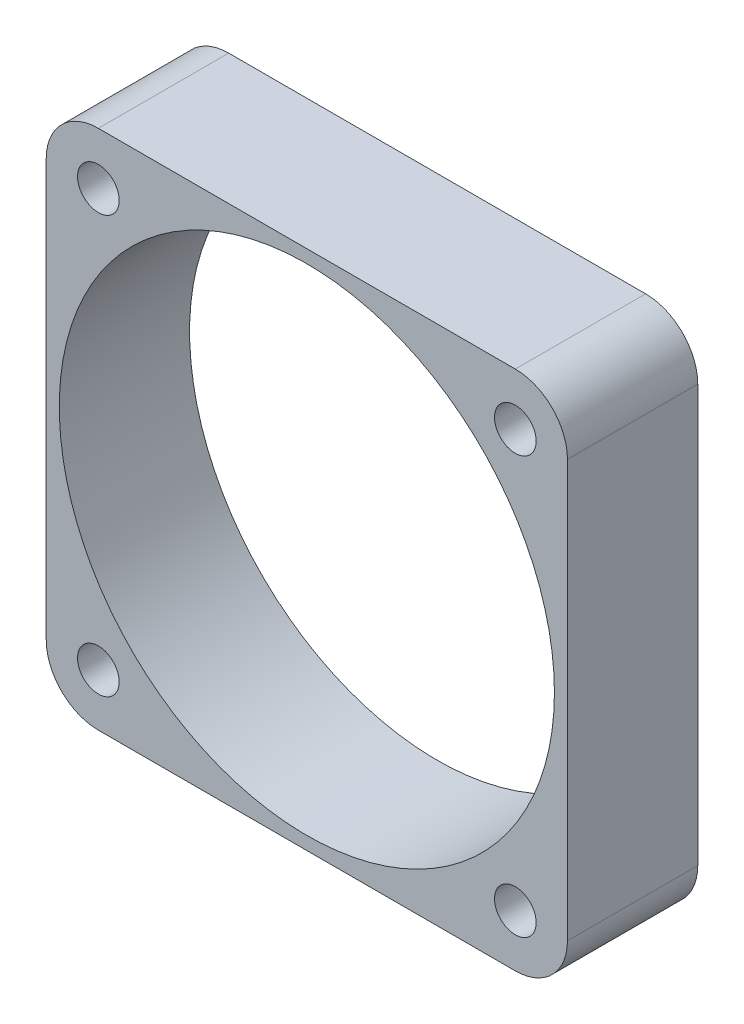
SolidWorks part; units mm, degrees
ref_plane "Front Plane" through (0, 0, 0) normal (0, 0, 1) x (1, 0, 0)
ref_plane "Top Plane" through (0, 0, 0) normal (0, 1, 0) x (1, 0, 0)
ref_plane "Right Plane" through (0, 0, 0) normal (1, 0, 0) x (0, 0, -1)
sketch "Sketch1" plane through (0, 0, 0) normal (0, 0, 1) x (1, 0, 0)
  line L0 (0, 0) -> (0, 20) construction
  line L1 (-20, 20) -> (20, 20) construction
  line L2 (-20, 20) -> (-20, -20) construction
  line L3 (-20, -20) -> (20, -20) construction
  line L4 (20, 20) -> (20, -20) construction
  line L5 (0, 0) -> (-20, 0) construction
  line L6 (-16, 20) -> (16, 20)
  line L7 (-16, 16) -> (16, 16) construction
  line L8 (-16, 16) -> (-16, -16) construction
  line L9 (-16, -16) -> (16, -16) construction
  line L10 (16, 16) -> (16, -16) construction
  line L11 (20, 16) -> (20, -16)
  line L12 (-20, -16) -> (-20, 16)
  line L13 (-16, -20) -> (16, -20)
  circle A0 centre (0, 0) radius 19
  circle A1 centre (-16, 16) radius 1.6
  circle A2 centre (16, 16) radius 1.6
  circle A3 centre (16, -16) radius 1.6
  circle A4 centre (-16, -16) radius 1.6
  arc A5 (-20, 16) -> (-16, 20) centre (-16, 16) cw
  arc A6 (16, 20) -> (20, 16) centre (16, 16) cw
  arc A7 (20, -16) -> (16, -20) centre (16, -16) cw
  arc A8 (-16, -20) -> (-20, -16) centre (-16, -16) cw
  dimension "D3" = 38
  dimension "D4" = 3.2
  dimension "D1" = 40
  dimension "D2" = 4
extrude "Boss-Extrude1" add sketch "Sketch1" along normal blind 10
